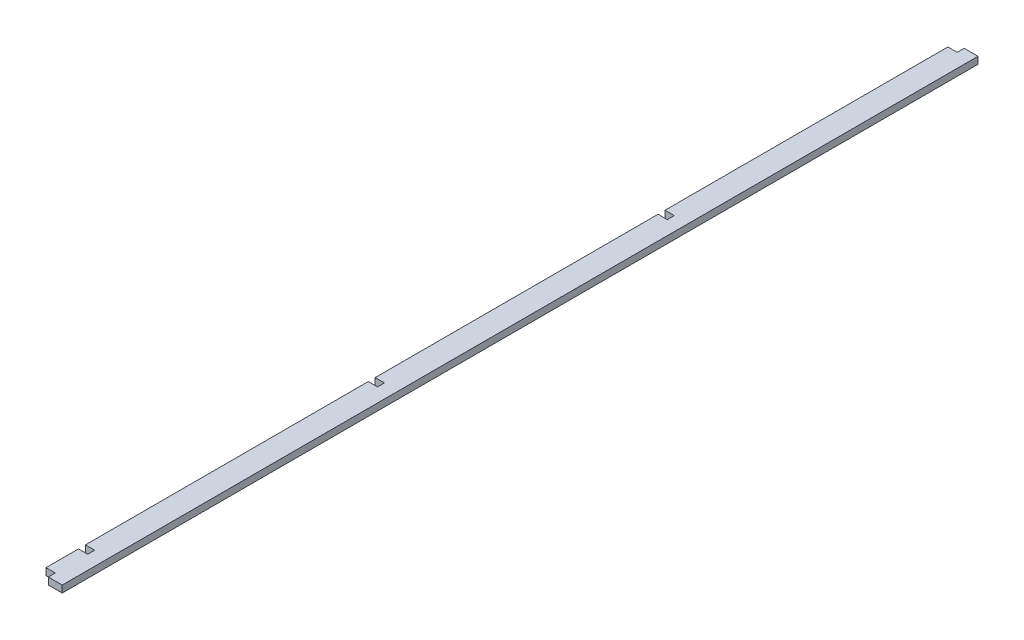
SolidWorks part; units mm, degrees
material "轻木"
ref_plane "前视基准面" through (0, 0, 0) normal (0, 0, 1) x (1, 0, 0)
ref_plane "上视基准面" through (0, 0, 0) normal (0, 1, 0) x (1, 0, 0)
ref_plane "右视基准面" through (0, 0, 0) normal (1, 0, 0) x (0, 0, -1)
other "Configuration Table"
sketch "草图1" plane through (0, 0, 1160.01) normal (0, 0, 1) x (1, 0, 0)
  line L1 (130.7876, -3.3897) -> (120.7876, -3.3897)
  line L2 (130.7876, -3.3897) -> (130.7876, -6.3897)
  line L3 (130.7876, -6.3897) -> (120.7876, -6.3897)
  line L4 (120.7876, -3.3897) -> (120.7876, -6.3897)
  dimension "D1" = 3
  dimension "D2" = 10
extrude "凸台-拉伸1" add sketch "草图1" against normal blind 395
sketch "草图2" plane through (0, -3.3897, 0) normal (0, 1, 0) x (1, 0, 0)
  line L0 (120.7876, -890.01) -> (124.7876, -890.01)
  line L9 (120.7876, -890.01) -> (120.7876, -893.01)
  line L22 (120.7876, -893.01) -> (124.7876, -893.01)
  line L23 (120.7876, -765.01) -> (124.7876, -765.01)
  line L28 (120.7876, -765.01) -> (120.7876, -768.01)
  line L29 (120.7876, -768.01) -> (124.7876, -768.01)
  line L30 (124.7876, -890.01) -> (124.7876, -893.01)
  line L39 (124.7876, -765.01) -> (124.7876, -768.01)
  line L40 (120.7876, -1015.01) -> (124.7876, -1015.01)
  line L41 (120.7876, -1015.01) -> (120.7876, -1018.01)
  line L42 (120.7876, -1018.01) -> (124.7876, -1018.01)
  line L43 (124.7876, -1015.01) -> (124.7876, -1018.01)
  line L44 (120.7876, -1140.01) -> (124.7876, -1140.01)
  line L45 (120.7876, -1140.01) -> (120.7876, -1143.01)
  line L46 (120.7876, -1143.01) -> (124.7876, -1143.01)
  line L47 (124.7876, -1140.01) -> (124.7876, -1143.01)
  line L48 (120.7876, -765.01) -> (120.7876, -890.01) construction
  line L49 (130.7876, -1160.01) -> (120.7876, -1160.01) construction
  line L50 (124.7876, -1160.01) -> (120.7876, -1160.01)
  line L51 (124.7876, -1160.01) -> (124.7876, -1157.01)
  line L52 (124.7876, -1157.01) -> (120.7876, -1157.01)
  line L53 (120.7876, -1160.01) -> (120.7876, -1157.01)
  line L54 (120.7876, -765.01) -> (120.7876, -1160.01) construction
  dimension "D2" = 3
  dimension "D4" = 4
  dimension "D1" = 4
  dimension "D3" = 125
  dimension "D5" = 17
  dimension "D6" = 4
extrude "切除-拉伸1" cut sketch "草图2" against normal through all
